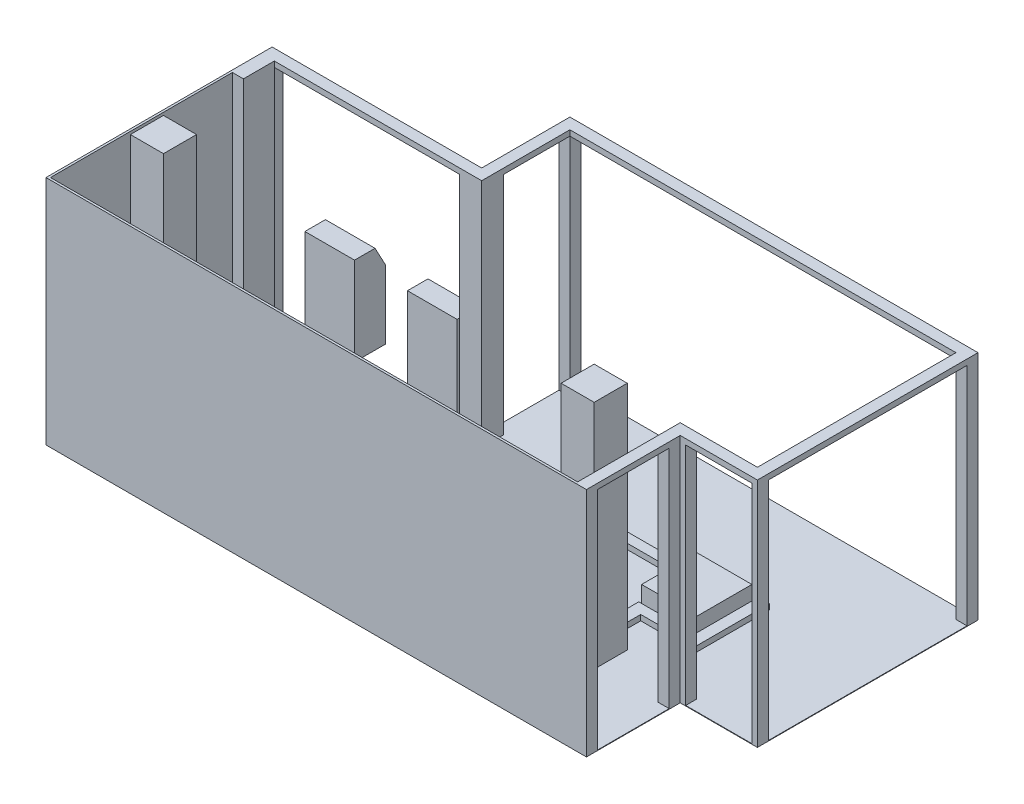
SolidWorks part; units mm, degrees
ref_plane "Alzado" through (0, 0, 0) normal (0, 0, 1) x (1, 0, 0)
ref_plane "Planta" through (0, 0, 0) normal (0, 1, 0) x (1, 0, 0)
ref_plane "Vista lateral" through (0, 0, 0) normal (1, 0, 0) x (0, 0, -1)
sketch "Croquis1" plane through (0, 0, 0) normal (0, 1, 0) x (1, 0, 0)
  line L0 (1253.5816, -550.3598) -> (1253.5816, -1400.3598)
  line L2 (-3646.4184, -250.3598) -> (-3646.4184, 649.6402)
  line L3 (-1746.4184, 1449.6402) -> (1953.5816, 1449.6402)
  line L4 (1953.5816, -550.3598) -> (1953.5816, 1449.6402)
  line L5 (-3626.4184, 549.6402) -> (-3626.4184, -1380.3598)
  line L6 (303.5816, -380.3598) -> (603.5816, -380.3598)
  line L9 (-1746.4184, 1449.6402) -> (-1746.4184, 649.6402)
  line L10 (-1746.4184, 649.6402) -> (-3646.4184, 649.6402)
  line L11 (1253.5816, -1400.3598) -> (-3646.4184, -1400.3598)
  line L12 (-3646.4184, -1400.3598) -> (-3646.4184, -250.3598)
  line L13 (1253.5816, -550.3598) -> (1953.5816, -550.3598)
  line L14 (303.5816, -380.3598) -> (303.5816, -680.3598)
  line L15 (303.5816, -680.3598) -> (603.5816, -680.3598)
  line L16 (603.5816, -380.3598) -> (603.5816, -680.3598)
  line L17 (303.5816, -380.3598) -> (603.5816, -680.3598) construction
  line L18 (303.5816, -680.3598) -> (603.5816, -380.3598) construction
  line L19 (-3626.4184, -1380.3598) -> (1153.5816, -1380.3598)
  line L20 (1153.5816, -1380.3598) -> (1153.5816, -450.3598)
  line L21 (1153.5816, -450.3598) -> (1853.5816, -450.3598)
  line L22 (1853.5816, -450.3598) -> (1853.5816, 1349.6402)
  line L23 (1853.5816, 1349.6402) -> (-1646.4184, 1349.6402)
  line L24 (-1646.4184, 1349.6402) -> (-1646.4184, 549.6402)
  line L25 (-1646.4184, 549.6402) -> (-3626.4184, 549.6402)
  point P0 (0, 0)
  point P3 (453.5816, -530.3598)
  point P6 (1253.5816, -550.3598)
  point P9 (-1746.4184, 1449.6402)
  dimension "D1" = 3700
  dimension "D2" = 4900
  dimension "D3" = 700
  dimension "D4" = 850
  dimension "D5" = 1900
  dimension "D6" = 800
  dimension "D7" = 2000
  dimension "D8" = 700
  dimension "D9" = 800
  dimension "D10" = 300
  dimension "D11" = 300
  dimension "D12" = 100
  dimension "D13" = 100
  dimension "D14" = 100
  dimension "D15" = 20
  dimension "D16" = 20
  dimension "D17" = 100
  dimension "D18" = 100
  dimension "D19" = 100
extrude "Saliente-Extruir1" add sketch "Croquis1" along normal blind 2100 contours L0 L13 L4 L3 L9 L10 L2 L12 L11 L25 L24 L23 L22 L21 L20 L19 L5 | L16 L6 L14 L15
sketch "Croquis3" plane through (0, 0, 0) normal (0, 1, 0) x (1, 0, 0)
  line L1 (-3601.4184, -380.3598) -> (-3301.4184, -380.3598)
  line L2 (-3601.4184, -380.3598) -> (-3601.4184, -680.3598)
  line L3 (-3601.4184, -680.3598) -> (-3301.4184, -680.3598)
  line L4 (-3301.4184, -380.3598) -> (-3301.4184, -680.3598)
  line L6 (-3626.4184, -1380.3598) -> (1153.5816, -1380.3598) construction
  line L7 (-3626.4184, 549.6402) -> (-3626.4184, -1380.3598) construction
  line L8 (-1646.4184, 549.6402) -> (-3626.4184, 549.6402) construction
  line L9 (-3526.4184, 549.6402) -> (-3626.4184, 549.6402)
  line L10 (-3526.4184, 549.6402) -> (-3526.4184, 269.6402)
  line L11 (-3526.4184, 269.6402) -> (-3626.4184, 269.6402)
  line L12 (-3626.4184, 549.6402) -> (-3626.4184, 269.6402)
  dimension "D1" = 300
  dimension "D2" = 300
  dimension "D3" = 700
  dimension "D4" = 25
  dimension "D5" = 100
  dimension "D6" = 280
extrude "Saliente-Extruir2" add sketch "Croquis3" along normal blind 2100 separate body
sketch "Croquis4" plane through (0, 0, 0) normal (0, 1, 0) x (1, 0, 0)
  line L0 (-3626.4184, 549.6402) -> (-3626.4184, -1380.3598) construction
  line L1 (-3596.4184, 173.8437) -> (-3416.4184, 173.8437)
  line L2 (-3596.4184, 173.8437) -> (-3596.4184, -6.1563)
  line L3 (-3596.4184, -6.1563) -> (-3416.4184, -6.1563)
  line L4 (-3416.4184, 173.8437) -> (-3416.4184, -6.1563)
  line L5 (-3596.4184, 173.8437) -> (-3416.4184, -6.1563) construction
  line L6 (-3596.4184, -6.1563) -> (-3416.4184, 173.8437) construction
  point P0 (-3506.4184, 83.8437)
  dimension "D1" = 180
  dimension "D2" = 180
  dimension "D3" = 120
extrude "Saliente-Extruir3" add sketch "Croquis4" along normal blind 200 separate body
sketch "Croquis6" plane through (1953.5816, 0, 0) normal (1, 0, 0) x (0, 0, -1)
  line L0 (-550.3598, 2100) -> (-550.3598, 0) construction
  line L1 (-450.3598, 0) -> (1349.6402, 0)
  line L2 (-450.3598, 0) -> (-450.3598, 2050)
  line L3 (-450.3598, 2050) -> (1349.6402, 2050)
  line L4 (1349.6402, 0) -> (1349.6402, 2050)
  line L5 (-450.3598, 0) -> (1349.6402, 2050) construction
  line L6 (-450.3598, 2050) -> (1349.6402, 0) construction
  line L7 (-550.3598, 2100) -> (1449.6402, 2100) construction
  line L8 (1449.6402, 2100) -> (1449.6402, 0) construction
  line L9 (-550.3598, 0) -> (1449.6402, 0) construction
  point P0 (449.6402, 1025)
  dimension "D1" = 100
  dimension "D2" = 50
  dimension "D3" = 100
  dimension "D4" = 0
extrude "Cortar-Extruir1" cut sketch "Croquis6" against normal up to surface (100 mm away) up to face at (1853.5816, 1050, -449.6402)
sketch "Croquis7" plane through (0, 0, 550.3598) normal (0, 0, 1) x (1, 0, 0)
  line L0 (1253.5816, 2100) -> (1253.5816, 0) construction
  line L1 (1303.5816, 0) -> (1903.5816, 0)
  line L2 (1303.5816, 0) -> (1303.5816, 2050)
  line L3 (1303.5816, 2050) -> (1903.5816, 2050)
  line L4 (1903.5816, 0) -> (1903.5816, 2050)
  line L5 (1303.5816, 0) -> (1903.5816, 2050) construction
  line L6 (1303.5816, 2050) -> (1903.5816, 0) construction
  line L7 (1253.5816, 2100) -> (1953.5816, 2100) construction
  line L8 (1953.5816, 2100) -> (1953.5816, 0) construction
  line L9 (1253.5816, 0) -> (1953.5816, 0) construction
  point P0 (1603.5816, 1025)
  dimension "D1" = 50
  dimension "D2" = 50
  dimension "D3" = 50
  dimension "D4" = 0
extrude "Cortar-Extruir2" cut sketch "Croquis7" against normal up to surface (100 mm away) up to face at (1653.5816, 1383.3333, 450.3598)
sketch "Croquis8" plane through (0, 0, -1449.6402) normal (0, 0, -1) x (-1, 0, 0)
  line L0 (1746.4184, 2100) -> (-1953.5816, 2100) construction
  line L1 (-1853.5816, 0) -> (1646.4184, 0)
  line L2 (-1853.5816, 0) -> (-1853.5816, 2050)
  line L3 (-1853.5816, 2050) -> (1646.4184, 2050)
  line L4 (1646.4184, 0) -> (1646.4184, 2050)
  line L5 (-1853.5816, 0) -> (1646.4184, 2050) construction
  line L6 (-1853.5816, 2050) -> (1646.4184, 0) construction
  line L7 (-1953.5816, 2100) -> (-1953.5816, 0) construction
  line L8 (1746.4184, 0) -> (-1953.5816, 0) construction
  line L9 (1746.4184, 2100) -> (1746.4184, 0) construction
  point P0 (-103.5816, 1025)
  dimension "D1" = 50
  dimension "D2" = 100
  dimension "D3" = 0
  dimension "D4" = 100
extrude "Cortar-Extruir3" cut sketch "Croquis8" against normal up to surface (100 mm away) up to face at (720.2483, 1383.3333, -1349.6402)
sketch "Croquis9" plane through (1253.5816, 0, 0) normal (1, 0, 0) x (0, 0, -1)
  line L0 (-1400.3598, 2100) -> (-1400.3598, 0) construction
  line L1 (-1300.3598, 0) -> (-650.3598, 0)
  line L2 (-1300.3598, 0) -> (-1300.3598, 2050)
  line L3 (-1300.3598, 2050) -> (-650.3598, 2050)
  line L4 (-650.3598, 0) -> (-650.3598, 2050)
  line L5 (-1300.3598, 0) -> (-650.3598, 2050) construction
  line L6 (-1300.3598, 2050) -> (-650.3598, 0) construction
  line L7 (-550.3598, 2100) -> (-1400.3598, 2100) construction
  line L8 (-550.3598, 2100) -> (-550.3598, 0) construction
  line L9 (-550.3598, 0) -> (-1400.3598, 0) construction
  point P0 (-975.3598, 1025)
  dimension "D1" = 100
  dimension "D2" = 100
  dimension "D3" = 50
  dimension "D4" = 0
extrude "Cortar-Extruir4" cut sketch "Croquis9" against normal up to surface (100 mm away) up to face at (1153.5816, 1050, 915.3598)
sketch "Croquis10" plane through (-1746.4184, 0, 0) normal (-1, 0, 0) x (0, 0, 1)
  line L0 (-1449.6402, 2100) -> (-1449.6402, 0) construction
  line L1 (-1349.6402, 0) -> (-749.6402, 0)
  line L2 (-1349.6402, 0) -> (-1349.6402, 2050)
  line L3 (-1349.6402, 2050) -> (-749.6402, 2050)
  line L4 (-749.6402, 0) -> (-749.6402, 2050)
  line L5 (-1349.6402, 0) -> (-749.6402, 2050) construction
  line L6 (-1349.6402, 2050) -> (-749.6402, 0) construction
  line L7 (-649.6402, 2100) -> (-649.6402, 0) construction
  line L8 (-1449.6402, 2100) -> (-649.6402, 2100) construction
  line L9 (-1449.6402, 0) -> (-649.6402, 0) construction
  point P0 (-1049.6402, 1025)
  dimension "D1" = 100
  dimension "D2" = 100
  dimension "D3" = 50
  dimension "D4" = 0
extrude "Cortar-Extruir5" cut sketch "Croquis10" against normal up to surface (100 mm away) up to face at (-1646.4184, 1383.3333, -1116.3068)
sketch "Croquis11" plane through (0, 0, -649.6402) normal (0, 0, -1) x (-1, 0, 0)
  line L0 (1746.4184, 2100) -> (1746.4184, 0) construction
  line L1 (1846.4184, 0) -> (3546.4184, 0)
  line L2 (1846.4184, 0) -> (1846.4184, 2050)
  line L3 (1846.4184, 2050) -> (3546.4184, 2050)
  line L4 (3546.4184, 0) -> (3546.4184, 2050)
  line L5 (1846.4184, 0) -> (3546.4184, 2050) construction
  line L6 (1846.4184, 2050) -> (3546.4184, 0) construction
  line L7 (3646.4184, 2100) -> (3646.4184, 0) construction
  line L8 (1746.4184, 2100) -> (3646.4184, 2100) construction
  line L9 (1746.4184, 0) -> (3646.4184, 0) construction
  point P0 (2696.4184, 1025)
  dimension "D1" = 100
  dimension "D2" = 100
  dimension "D3" = 50
  dimension "D4" = 0
extrude "Cortar-Extruir6" cut sketch "Croquis11" against normal up to surface (100 mm away) up to face at (-2636.4184, 1050, -549.6402)
sketch "Croquis12" plane through (0, 0, 0) normal (0, 1, 0) x (1, 0, 0)
  line L0 (-3646.4184, 649.6402) -> (-3646.4184, -1400.3598)
  line L1 (-3646.4184, -1400.3598) -> (1253.5816, -1400.3598)
  line L2 (1253.5816, -1400.3598) -> (1253.5816, -550.3598)
  line L3 (1253.5816, -550.3598) -> (1953.5816, -550.3598)
  line L4 (1953.5816, -550.3598) -> (1953.5816, 1449.6402)
  line L5 (1953.5816, -550.3598) -> (1953.5816, 1449.6402) construction
  line L6 (1953.5816, 1449.6402) -> (-1746.4184, 1449.6402)
  line L7 (-1746.4184, 1449.6402) -> (-1746.4184, 649.6402)
  line L8 (-1746.4184, 649.6402) -> (-3646.4184, 649.6402)
extrude "Saliente-Extruir5" add sketch "Croquis12" along normal blind 5
sketch "Croquis13" plane through (0, 5, 0) normal (0, 1, 0) x (1, 0, 0)
  line L0 (1853.5816, 1349.6402) -> (-1646.4184, 1349.6402) construction
  line L1 (303.5816, 549.6402) -> (803.5816, 549.6402)
  line L2 (303.5816, 549.6402) -> (303.5816, 49.6402)
  line L3 (303.5816, 49.6402) -> (803.5816, 49.6402)
  line L4 (803.5816, 549.6402) -> (803.5816, 49.6402)
  line L5 (303.5816, 549.6402) -> (803.5816, 49.6402) construction
  line L6 (303.5816, 49.6402) -> (803.5816, 549.6402) construction
  line L7 (-1646.4184, 1349.6402) -> (-1646.4184, 549.6402) construction
  point P0 (553.5816, 299.6402)
  dimension "D1" = 500
  dimension "D2" = 500
  dimension "D3" = 1050
  dimension "D4" = 2200
extrude "Saliente-Extruir6" add sketch "Croquis13" along normal blind 150
sketch "Croquis14" plane through (0, 5, 0) normal (0, 1, 0) x (1, 0, 0)
  line L0 (1153.5816, -1380.3598) -> (-3626.4184, -1380.3598) construction
  line L1 (-2485.7395, -130.3598) -> (-1985.7395, -130.3598)
  line L2 (-2485.7395, -130.3598) -> (-2485.7395, -630.3598)
  line L3 (-2485.7395, -630.3598) -> (-1985.7395, -630.3598)
  line L4 (-1985.7395, -130.3598) -> (-1985.7395, -630.3598)
  line L5 (-2485.7395, -130.3598) -> (-1985.7395, -630.3598) construction
  line L6 (-2485.7395, -630.3598) -> (-1985.7395, -130.3598) construction
  point P0 (-2235.7395, -380.3598)
  dimension "D1" = 500
  dimension "D2" = 500
  dimension "D3" = 1000
extrude "Saliente-Extruir7" add sketch "Croquis14" along normal blind 200
sketch "Croquis15" plane through (0, 0, 0) normal (0, 1, 0) x (1, 0, 0)
  line L0 (-1746.4184, 649.6402) -> (-3646.4184, 649.6402) construction
  line L1 (-3349.2502, 649.6402) -> (-2899.2502, 649.6402)
  line L2 (-3349.2502, 649.6402) -> (-3349.2502, 929.6402)
  line L3 (-3349.2502, 929.6402) -> (-2899.2502, 929.6402)
  line L4 (-2899.2502, 649.6402) -> (-2899.2502, 929.6402)
  line L6 (-2419.2502, 649.6402) -> (-1969.2502, 649.6402)
  line L7 (-2419.2502, 649.6402) -> (-2419.2502, 929.6402)
  line L8 (-2419.2502, 929.6402) -> (-1969.2502, 929.6402)
  line L9 (-1969.2502, 649.6402) -> (-1969.2502, 929.6402)
  dimension "D1" = 450
  dimension "D2" = 280
  dimension "D3" = 480
extrude "Saliente-Extruir8" add sketch "Croquis15" along normal blind 800
sketch "Croquis16" plane through (-3349.2502, 0, 0) normal (-1, 0, 0) x (0, 0, 1)
  line L0 (-929.6402, 623.7857) -> (-835.6667, 800)
  line L1 (-929.6402, 800) -> (-929.6402, 0) construction
  line L2 (-929.6402, 800) -> (-649.6402, 800) construction
  line L3 (-835.6667, 800) -> (-929.6402, 800)
  line L4 (-929.6402, 800) -> (-929.6402, 623.7857)
extrude "Cortar-Extruir7" cut sketch "Croquis16" against normal up to surface (1380 mm away) up to face at (-1969.2502, 321, -761.6402)
sketch "Croquis19" plane through (0, 5, 0) normal (0, 1, 0) x (1, 0, 0)
  line L0 (327.4164, -380.3598) -> (327.4164, 0)
  line L1 (303.5816, -380.3598) -> (603.5816, -380.3598) construction
  line L2 (303.5816, -380.3598) -> (603.5816, -380.3598) construction
  line L5 (327.4164, 0) -> (833.3797, 0)
  line L6 (833.3797, 0) -> (833.3797, 577.8267)
  line L7 (833.3797, 577.8267) -> (934.5724, 577.8267)
  line L8 (934.5724, 577.8267) -> (934.5724, -90.0448)
  line L9 (934.5724, -90.0448) -> (435.3553, -90.0448)
  line L10 (435.3553, -90.0448) -> (435.3553, -380.3598)
  line L11 (435.3553, -380.3598) -> (327.4164, -380.3598)
extrude "Saliente-Extruir11" add sketch "Croquis19" along normal blind 50
sketch "Croquis20" plane through (0, 5, 0) normal (0, 1, 0) x (1, 0, 0)
  line L0 (-2236.1309, 549.6402) -> (-2236.1309, 407.9704)
  line L1 (-2236.1309, 407.9704) -> (145.2697, 407.9704)
  line L2 (145.2697, 407.9704) -> (145.2697, 497.9704)
  line L3 (145.2697, 497.9704) -> (-2134.9383, 497.9704)
  line L4 (-2134.9383, 497.9704) -> (-2134.9383, 549.6402)
  line L5 (-1646.4184, 549.6402) -> (-3526.4184, 549.6402) construction
  line L6 (-2236.1309, 549.6402) -> (-2134.9383, 549.6402)
  dimension "D1" = 90
extrude "Saliente-Extruir12" add sketch "Croquis20" along normal blind 50
sketch "Croquis21" plane through (0, 5, 0) normal (0, 1, 0) x (1, 0, 0)
  line L0 (327.4164, -306.2274) -> (-1959.5377, -306.2274)
  line L1 (327.4164, 0) -> (327.4164, -380.3598) construction
  line L2 (327.4164, -206.2274) -> (-1865.0912, -206.2274)
  line L3 (-1865.0912, -206.2274) -> (-1865.0912, 0)
  line L4 (-1865.0912, 0) -> (-3060.3572, 0)
  line L5 (-3060.3572, 0) -> (-3060.3572, 549.6402)
  line L6 (-1646.4184, 549.6402) -> (-3526.4184, 549.6402) construction
  line L7 (-3060.3572, 549.6402) -> (-3160.3572, 549.6402)
  line L8 (-3160.3572, 549.6402) -> (-3160.3572, -100)
  line L9 (-3160.3572, -100) -> (-1959.5377, -100)
  line L10 (-1959.5377, -100) -> (-1959.5377, -306.2274)
  line L11 (327.4164, -306.2274) -> (327.4164, -206.2274)
  dimension "D1" = 100
  dimension "D2" = 100
  dimension "D3" = 100
extrude "Saliente-Extruir13" add sketch "Croquis21" along normal blind 50
sketch "Croquis22" plane through (0, 5, 0) normal (0, 1, 0) x (1, 0, 0)
  line L0 (1153.5816, -1380.3598) -> (-3626.4184, -1380.3598) construction
  line L1 (432.2214, -830.3598) -> (682.2214, -830.3598)
  line L2 (432.2214, -830.3598) -> (432.2214, -1030.3598)
  line L3 (432.2214, -1030.3598) -> (682.2214, -1030.3598)
  line L4 (682.2214, -830.3598) -> (682.2214, -1030.3598)
  line L5 (432.2214, -830.3598) -> (682.2214, -1030.3598) construction
  line L6 (432.2214, -1030.3598) -> (682.2214, -830.3598) construction
  point P0 (557.2214, -930.3598)
  dimension "D1" = 450
  dimension "D2" = 200
  dimension "D3" = 250
extrude "Saliente-Extruir14" add sketch "Croquis22" along normal blind 150
sketch "Croquis23" plane through (0, 5, 0) normal (0, 1, 0) x (1, 0, 0)
  line L1 (425.4629, -1213.0785) -> (125.4629, -1213.0785)
  line L2 (425.4629, -1213.0785) -> (425.4629, -913.0785)
  line L3 (425.4629, -913.0785) -> (125.4629, -913.0785)
  line L4 (125.4629, -1213.0785) -> (125.4629, -913.0785)
  line L5 (425.4629, -1213.0785) -> (125.4629, -913.0785) construction
  line L6 (425.4629, -913.0785) -> (125.4629, -1213.0785) construction
  point P0 (275.4629, -1063.0785)
  dimension "D1" = 300
  dimension "D2" = 300
extrude "Saliente-Extruir15" add sketch "Croquis23" along normal blind 50
